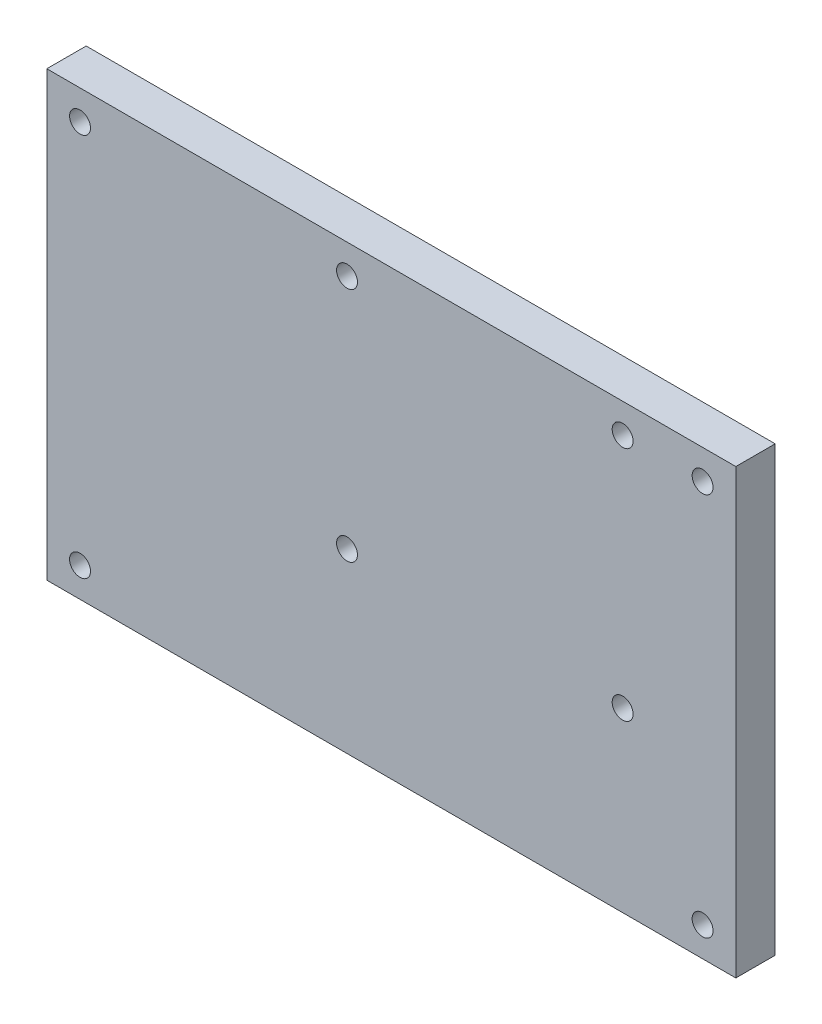
SolidWorks part; units mm, degrees
ref_plane "Front Plane" through (0, 0, 0) normal (0, 0, 1) x (1, 0, 0)
ref_plane "Top Plane" through (0, 0, 0) normal (0, 1, 0) x (1, 0, 0)
ref_plane "Right Plane" through (0, 0, 0) normal (1, 0, 0) x (0, 0, -1)
other "Configuration Table"
sketch "Sketch1" plane through (0, 0, 0) normal (0, 0, 1) x (1, 0, 0)
  line L1 (0, 0) -> (444.5, 0)
  line L2 (0, 0) -> (0, 285.75)
  line L3 (0, 285.75) -> (444.5, 285.75)
  line L4 (444.5, 0) -> (444.5, 285.75)
extrude "Boss-Extrude1" add sketch "Sketch1" along normal blind 25.4
sketch "Sketch2" plane through (0, 0, 0) normal (0, 0, 1) x (1, 0, 0)
  circle A0 centre (21.4376, 266.7) radius 6.7437
  circle A1 centre (423.0624, 266.7) radius 6.7437
  circle A2 centre (21.4376, 19.05) radius 6.7437
  circle A3 centre (423.0624, 19.05) radius 6.7437
extrude "Cut-Extrude1" cut sketch "Sketch2" along normal through all
sketch "Sketch3" plane through (0, 0, 0) normal (0, 0, 1) x (1, 0, 0)
  circle A0 centre (21.4376, 266.7) radius 9.525
  circle A1 centre (423.0624, 266.7) radius 9.525
  circle A2 centre (21.4376, 19.05) radius 9.525
  circle A3 centre (423.0624, 19.05) radius 9.525
extrude "Cut-Extrude2" cut sketch "Sketch3" along normal blind 7.62
sketch "Sketch4" plane through (0, 0, 0) normal (0, 0, 1) x (1, 0, 0)
  circle A0 centre (193.675, 114.3) radius 6.7437
  circle A1 centre (371.475, 114.3) radius 6.7437
  circle A2 centre (193.675, 266.7) radius 6.7437
  circle A3 centre (371.475, 266.7) radius 6.7437
extrude "Cut-Extrude3" cut sketch "Sketch4" along normal through all
